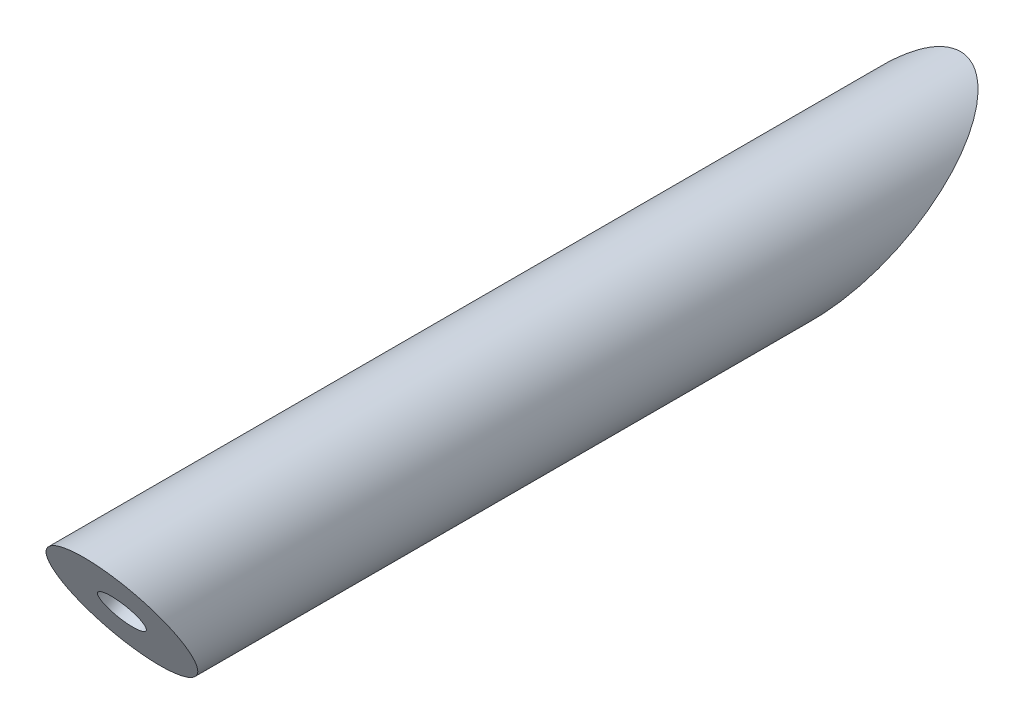
SolidWorks part; units mm, degrees
ref_plane "Front Plane" through (0, 0, 0) normal (0, 0, 1) x (1, 0, 0)
ref_plane "Top Plane" through (0, 0, 0) normal (0, 1, 0) x (1, 0, 0)
ref_plane "Right Plane" through (0, 0, 0) normal (1, 0, 0) x (0, 0, -1)
sketch "Sketch2" plane through (0, 0, 0) normal (0, 0, 1) x (1, 0, 0)
  circle A0 centre (0, 0) radius 7.5
  dimension "D1" = 15
extrude "Boss-Extrude1" add sketch "Sketch2" along normal blind 100
sketch "Sketch3" plane through (0, 0, 0) normal (1, 0, 0) x (0, 0, -1)
  line L0 (-100, 7.5) -> (-86.5722, -15.7576)
  line L1 (-86.5722, -15.7576) -> (-93.9682, -20.0277)
  line L2 (-93.9682, -20.0277) -> (-105.5312, 0)
  line L3 (-105.5312, 0) -> (-100, 7.5)
  line L4 (0, 7.5) -> (-100, 7.5) construction
  line L5 (0, 7.5) -> (-26.8368, -7.9942)
  line L6 (-26.8368, -7.9942) -> (-23.7886, -13.2739)
  line L7 (-23.7886, -13.2739) -> (1.512, -9.2436)
  line L8 (1.512, -9.2436) -> (5.3245, -3.175)
  line L9 (5.3245, -3.175) -> (0, 7.5)
  dimension "D1" = 60
  dimension "D2" = 30
extrude "Cut-Extrude1" cut sketch "Sketch3" against normal through all both and the other way through all
sketch "Sketch4" plane through (0, -41.4263, 71.7524) normal (0, -0.5, 0.866) x (1, 0, 0)
  circle A1 centre (0, 47.8349) radius 2.5
  dimension "D1" = 5
extrude "Cut-Extrude2" cut sketch "Sketch4" against normal blind 10 contours A1
sketch "Sketch5" plane through (0, 5.625, 3.2476) normal (0, -0.866, -0.5) x (1, 0, 0)
  circle A0 centre (0, 11.25) radius 2.5
  dimension "D1" = 5
extrude "Cut-Extrude3" cut sketch "Sketch5" against normal blind 5
